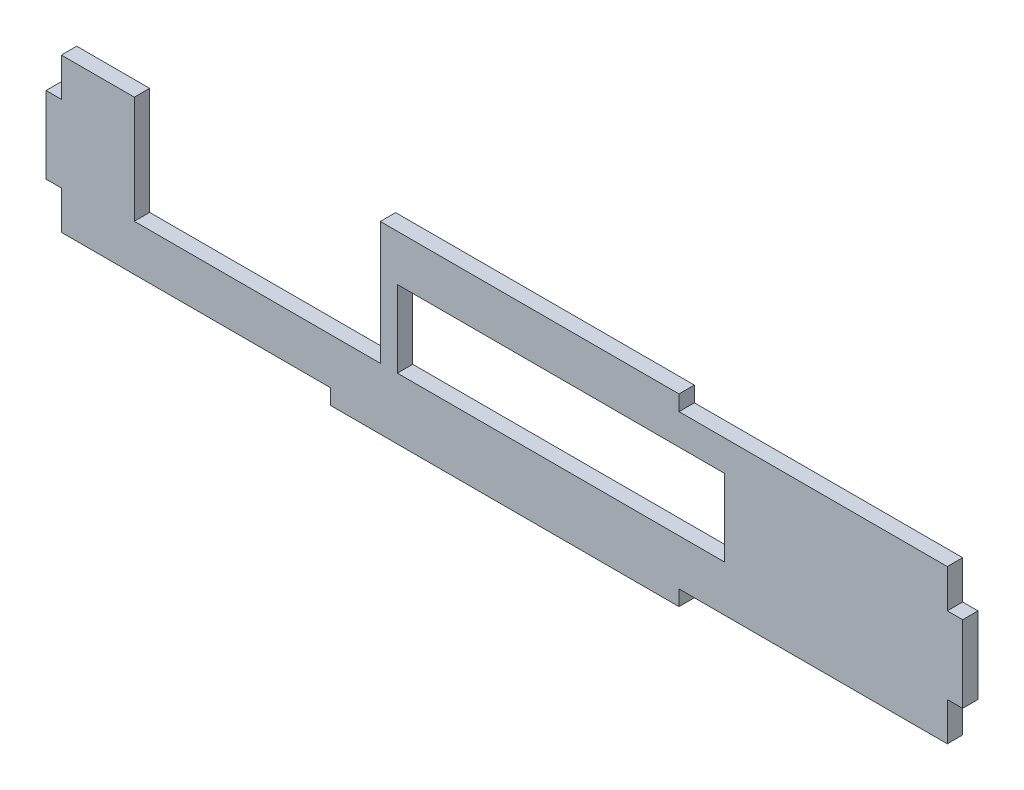
SolidWorks part; units mm, degrees
ref_plane "Front Plane" through (0, 0, 0) normal (0, 0, 1) x (1, 0, 0)
ref_plane "Top Plane" through (0, 0, 0) normal (0, 1, 0) x (1, 0, 0)
ref_plane "Right Plane" through (0, 0, 0) normal (1, 0, 0) x (0, 0, -1)
sketch "Sketch1" plane through (0, 0, 0) normal (0, 0, 1) x (1, 0, 0)
  line L0 (0, 20) -> (9.5, 20)
  line L5 (9.5, 5.9995) -> (41.5498, 5.9995)
  line L6 (9.5, 5.9995) -> (9.5, 20)
  line L8 (41.5498, 5.9995) -> (41.5498, 20)
  line L9 (86.41, 6) -> (43.7723, 6)
  line L10 (86.41, 6) -> (86.41, 16)
  line L11 (86.41, 16) -> (43.7723, 16)
  line L12 (43.7723, 6) -> (43.7723, 16)
  line L14 (0, 0) -> (35.0498, 0)
  line L15 (35.0498, 0) -> (35.0498, -2.0005)
  line L16 (35.0498, -2.0005) -> (80.4598, -2.0005)
  line L17 (80.4598, -2.0005) -> (80.4598, 0)
  line L18 (80.4598, 0) -> (115.41, 0)
  line L19 (0, 0) -> (0, 5)
  line L20 (0, 5) -> (-2, 5)
  line L21 (-2, 5) -> (-2, 15)
  line L22 (-2, 15) -> (0, 15)
  line L23 (0, 15) -> (0, 20)
  line L24 (115.41, 0) -> (115.41, 5)
  line L25 (115.41, 5) -> (117.41, 5)
  line L26 (117.41, 5) -> (117.41, 15)
  line L27 (117.41, 15) -> (115.41, 15)
  line L28 (115.41, 15) -> (115.41, 20)
  line L29 (80.4598, 20) -> (80.4598, 22)
  line L30 (80.4598, 22) -> (41.5498, 22)
  line L31 (41.5498, 22) -> (41.5498, 20)
  line L32 (80.4598, 20) -> (115.41, 20)
  point P27 (0, 0)
  dimension "D1" = 9.5
  dimension "D2" = 115.41
extrude "Boss-Extrude1" add sketch "Sketch1" along normal blind 2
